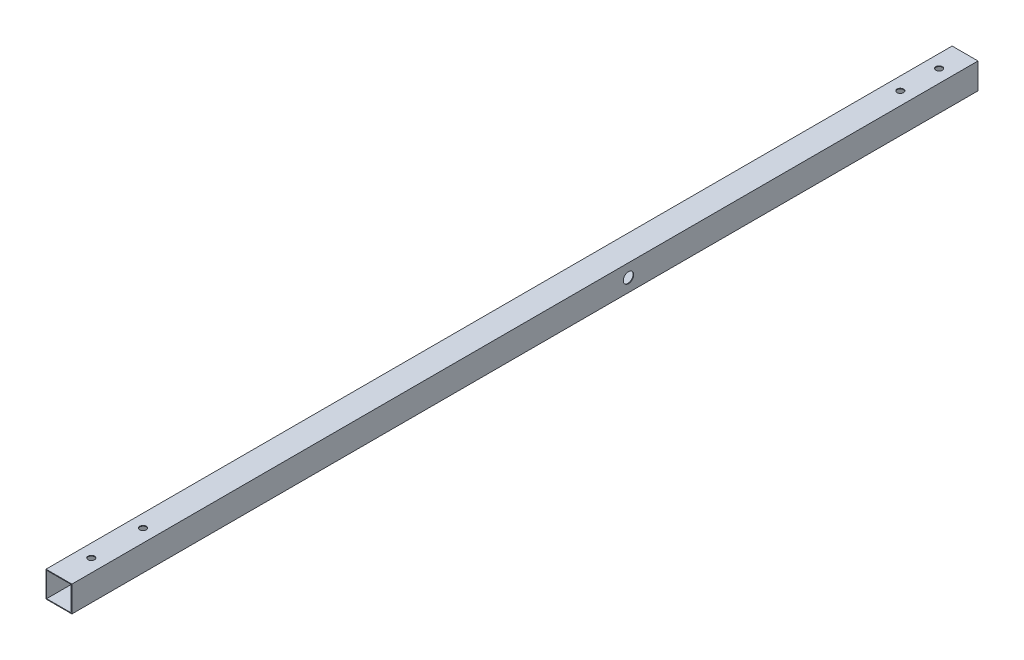
SolidWorks part; units mm, degrees
ref_plane "Front Plane" through (0, 0, 0) normal (0, 0, 1) x (1, 0, 0)
ref_plane "Top Plane" through (0, 0, 0) normal (0, 1, 0) x (1, 0, 0)
ref_plane "Right Plane" through (0, 0, 0) normal (1, 0, 0) x (0, 0, -1)
sketch "Sketch2" plane through (0, 0, 0) normal (0, 0, 1) x (1, 0, 0)
  line L1 (-10, 10) -> (10, 10)
  line L2 (-10, 10) -> (-10, -10)
  line L3 (-10, -10) -> (10, -10)
  line L4 (10, 10) -> (10, -10)
  line L5 (-10, 10) -> (10, -10) construction
  line L6 (-10, -10) -> (10, 10) construction
  point P0 (0, 0)
  dimension "D1" = 20
  dimension "D2" = 20
extrude "Boss-Extrude1" add sketch "Sketch2" along normal blind 700
sketch "Sketch3" plane through (0, 0, 0) normal (0, 0, -1) x (-1, 0, 0)
  line L1 (-9.5, 9.5) -> (9.5, 9.5)
  line L2 (-9.5, 9.5) -> (-9.5, -9.5)
  line L3 (-9.5, -9.5) -> (9.5, -9.5)
  line L4 (9.5, 9.5) -> (9.5, -9.5)
  line L5 (-9.5, 9.5) -> (9.5, -9.5) construction
  line L6 (-9.5, -9.5) -> (9.5, 9.5) construction
  point P0 (0, 0)
  dimension "D1" = 19
  dimension "D2" = 19
extrude "Cut-Extrude1" cut sketch "Sketch3" against normal blind 700
sketch "Sketch5" plane through (0, -10, 0) normal (0, -1, 0) x (1, 0, 0)
  line L0 (0, 700) -> (0, 447.3476) construction
  line L1 (-10, 700) -> (10, 700) construction
  circle A0 centre (0, 635) radius 2.5
  circle A1 centre (0, 675) radius 2.5
  dimension "D1" = 5
  dimension "D3" = 5
  dimension "D4" = 40
  dimension "D2" = 65
extrude "Cut-Extrude2" cut sketch "Sketch5" against normal blind 20
sketch "Sketch6" plane through (10, 0, 0) normal (1, 0, 0) x (0, 0, -1)
  line L0 (0, 0) -> (-700, 0) construction
  line L1 (-700, -10) -> (-700, 10) construction
  line L2 (0, 10) -> (0, -10) construction
  circle A0 centre (-270, 0) radius 4
  dimension "D1" = 8
  dimension "D2" = 270
extrude "Cut-Extrude3" cut sketch "Sketch6" against normal blind 20
sketch "Sketch7" plane through (0, -10, 0) normal (0, -1, 0) x (1, 0, 0)
  line L0 (0, 0) -> (0, 700) construction
  line L1 (-10, 700) -> (10, 700) construction
  line L2 (10, 0) -> (-10, 0) construction
  circle A0 centre (0, 20) radius 2.5
  circle A1 centre (0, 50) radius 2.5
  dimension "D1" = 5
  dimension "D2" = 5
  dimension "D3" = 30
  dimension "D4" = 20
extrude "Cut-Extrude4" cut sketch "Sketch7" against normal blind 20
